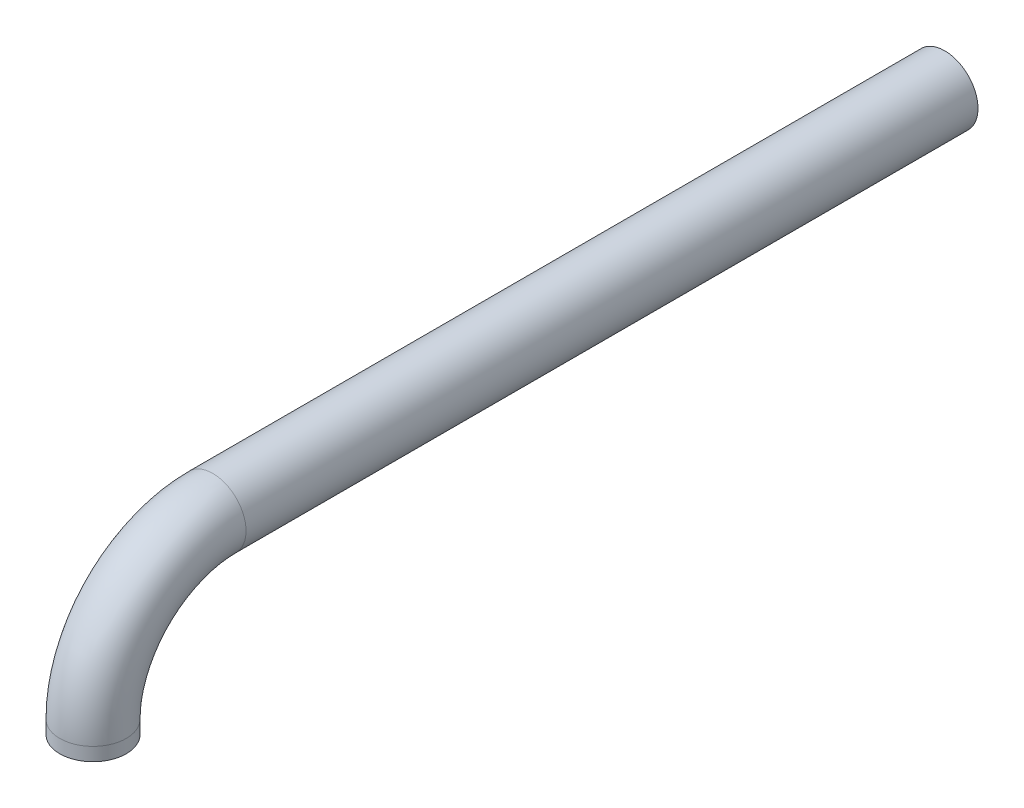
SolidWorks part; units mm, degrees
ref_plane "Front" through (0, 0, 0) normal (0, 0, 1) x (1, 0, 0)
ref_plane "Top" through (0, 0, 0) normal (0, 1, 0) x (1, 0, 0)
ref_plane "Right" through (0, 0, 0) normal (1, 0, 0) x (0, 0, -1)
sketch "Skizze1" plane through (0, 0, 0) normal (1, 0, 0) x (0, 0, -1)
  line L0 (0, 0) -> (0, 0.5)
  line L1 (4.5, 5) -> (32, 5)
  arc A0 (0, 0.5) -> (4.5, 5) centre (4.5, 0.5) cw
  point P6 (0, 5)
  dimension "D3" = 4.5
  dimension "D1" = 5
  dimension "D2" = 32
sketch "Skizze2" plane through (0, 0, 0) normal (0, 1, 0) x (1, 0, 0)
  circle A0 centre (0, 0) radius 1
  circle A1 centre (0, 0) radius 1.25
  dimension "D1" = 2.5
  dimension "D2" = 2
sweep "Austragung1" add profiles "Skizze2" path "Skizze1"
